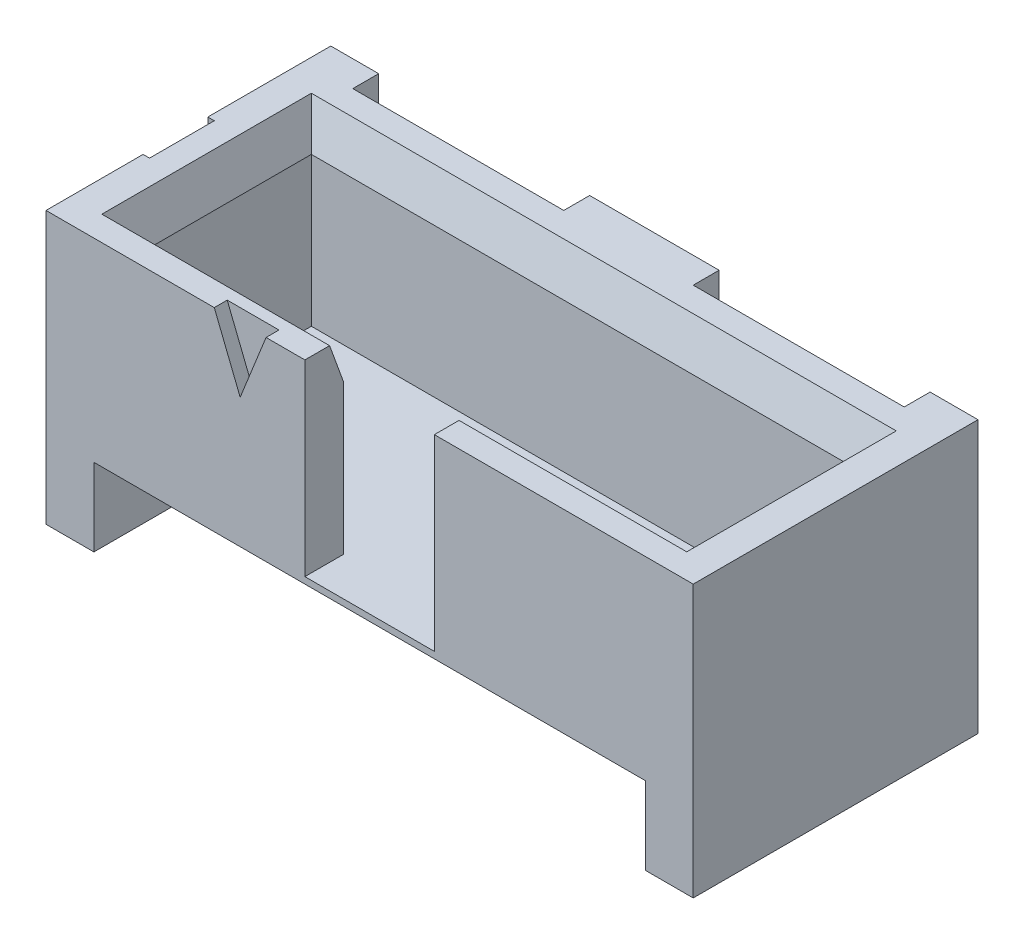
SolidWorks part; units mm, degrees
ref_plane "Front Plane" through (0, 0, 0) normal (0, 0, 1) x (1, 0, 0)
ref_plane "Top Plane" through (0, 0, 0) normal (0, 1, 0) x (1, 0, 0)
ref_plane "Right Plane" through (0, 0, 0) normal (1, 0, 0) x (0, 0, -1)
ref_plane "Plane1" through (0, 0, -3.048) normal (0, 0, 1) x (1, 0, 0)
sketch "Sketch1" plane through (0, 0, -3.048) normal (0, 0, 1) x (1, 0, 0)
  line L0 (-6.35, 5.334) -> (-6.35, 0)
  line L1 (-6.35, 0) -> (6.35, 0)
  line L2 (6.35, 0) -> (6.35, 5.334)
  line L3 (6.35, 5.334) -> (-6.35, 5.334)
extrude "Boss-Extrude1" add sketch "Sketch1" along normal blind 5.588
ref_plane "Plane2" through (0, 0, 0) normal (1, 0, 0) x (0, 0, -1)
sketch "Sketch2" plane through (0, 0, 0) normal (1, 0, 0) x (0, 0, -1)
  line L0 (-2.54, 1.524) -> (-2.54, 0)
  line L1 (-2.54, 0) -> (3.048, 0)
  line L2 (3.048, 0) -> (3.048, 2.032)
  line L3 (3.048, 2.032) -> (1.524, 0.508)
  line L4 (1.524, 0.508) -> (-1.524, 0.508)
  line L5 (-1.524, 0.508) -> (-2.54, 1.524)
extrude "Cut-Extrude1" cut sketch "Sketch2" against normal blind 5.4102 and the other way blind 5.4102
ref_plane "Plane3" through (0, 4.572, 0) normal (0, 1, 0) x (1, 0, 0)
sketch "Sketch3" plane through (0, 4.572, 0) normal (0, 1, 0) x (1, 0, 0)
  line L0 (-5.461, 1.778) -> (-5.461, -1.778)
  line L1 (-5.461, -1.778) -> (5.461, -1.778)
  line L2 (5.461, -1.778) -> (5.461, 1.778)
  line L3 (5.461, 1.778) -> (-5.461, 1.778)
extrude "Cut-Extrude2" cut sketch "Sketch3" along normal blind 0.762 draft 20 draft outward yes
ref_plane "Plane4" through (0, 0, 0) normal (0, 0, 1) x (1, 0, 0)
sketch "Sketch4" plane through (0, 0, 0) normal (0, 0, 1) x (1, 0, 0)
  line L0 (-1.27, 5.334) -> (-1.27, 1.651)
  line L1 (-1.27, 1.651) -> (1.27, 1.651)
  line L2 (1.27, 1.651) -> (1.27, 5.334)
  line L3 (1.27, 5.334) -> (-1.27, 5.334)
extrude "Cut-Extrude3" cut sketch "Sketch4" along normal blind 2.54
ref_plane "Plane5" through (0, 0, 2.54) normal (0, 0, 1) x (1, 0, 0)
sketch "Sketch5" plane through (0, 0, 2.54) normal (0, 0, 1) x (1, 0, 0)
  line L0 (-3.048, 5.334) -> (-2.54, 4.064)
  line L1 (-2.54, 4.064) -> (-2.032, 5.334)
  line L2 (-2.032, 5.334) -> (-3.048, 5.334)
extrude "Cut-Extrude4" cut sketch "Sketch5" against normal blind 0.254
ref_plane "Plane6" through (0, 5.334, 0) normal (0, 1, 0) x (1, 0, 0)
sketch "Sketch6" plane through (0, 5.334, 0) normal (0, 1, 0) x (1, 0, 0)
  line L0 (-5.461, 1.778) -> (-5.461, -1.778)
  line L1 (-5.461, -1.778) -> (5.461, -1.778)
  line L2 (5.461, -1.778) -> (5.461, 1.778)
  line L3 (5.461, 1.778) -> (-5.461, 1.778)
extrude "Cut-Extrude5" cut sketch "Sketch6" against normal blind 3.683
ref_plane "Plane7" through (0, 0, 0) normal (0, 1, 0) x (1, 0, 0)
sketch "Sketch7" plane through (0, 0, 0) normal (0, 1, 0) x (1, 0, 0)
  line L0 (-6.858, 3.302) -> (-6.858, -3.048)
  line L1 (-6.858, -3.048) -> (6.858, -3.048)
  line L2 (6.858, -3.048) -> (6.858, 3.302)
  line L3 (6.858, 3.302) -> (-6.858, 3.302)
  line L4 (-6.604, -0.635) -> (-6.604, -2.794)
  line L5 (-6.604, -2.794) -> (6.604, -2.794)
  line L6 (6.604, -2.794) -> (6.604, 3.048)
  line L7 (6.604, 3.048) -> (5.4102, 3.048)
  line L8 (5.4102, 3.048) -> (5.4102, 2.54)
  line L9 (5.4102, 2.54) -> (1.27, 2.54)
  line L10 (1.27, 2.54) -> (1.27, 3.048)
  line L11 (1.27, 3.048) -> (-1.27, 3.048)
  line L12 (-1.27, 3.048) -> (-1.27, 2.54)
  line L13 (-1.27, 2.54) -> (-5.4102, 2.54)
  line L14 (-5.4102, 2.54) -> (-5.4102, 3.048)
  line L15 (-5.4102, 3.048) -> (-6.604, 3.048)
  line L16 (-6.604, 3.048) -> (-6.604, 0.635)
  line L17 (-6.604, 0.635) -> (-6.223, 0.635)
  line L18 (-6.223, 0.635) -> (-6.223, -0.635)
  line L19 (-6.223, -0.635) -> (-6.604, -0.635)
extrude "Cut-Extrude6" cut sketch "Sketch7" along normal blind 5.334
